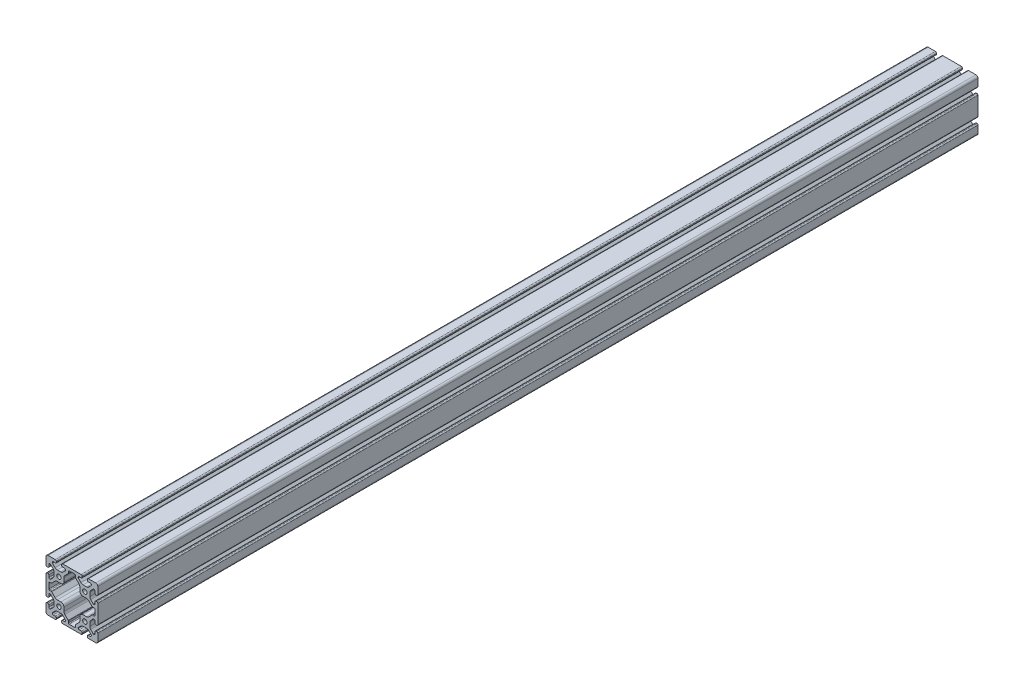
SolidWorks part; units mm, degrees
material "6061 Alloy"
ref_plane "Front Plane" through (0, 0, 0) normal (0, 0, 1) x (1, 0, 0)
ref_plane "Top Plane" through (0, 0, 0) normal (0, 1, 0) x (1, 0, 0)
ref_plane "Right Plane" through (0, 0, 0) normal (1, 0, 0) x (0, 0, -1)
sketch "Sketch1" plane through (0, 0, 0) normal (0, 0, 1) x (1, 0, 0)
  line L0 (0, -40) -> (0, 40) construction
  line L1 (0, 0) -> (-43.5804, 43.5804) construction
  line L2 (-20, 20) -> (-47.7323, 20) construction
  line L3 (-20, 20) -> (3.796, 43.796) construction
  line L4 (-20, 20) -> (-20, 43.5758) construction
  line L5 (-20, -27.7) -> (-20, -47.5576) construction
  line L7 (-36.8718, 24) -> (-28.8718, 24) construction
  line L8 (-36.8718, 24) -> (-36.8718, 16) construction
  line L9 (-36.8718, 16) -> (-28.8718, 16) construction
  line L10 (-28.8718, 24) -> (-28.8718, 16) construction
  line L11 (-36.8718, 24) -> (-28.8718, 16) construction
  line L12 (-36.8718, 16) -> (-28.8718, 24) construction
  line L131 (29.0912, 26.0365) -> (33.0827, 30.028)
  line L132 (27.7, 17.3222) -> (27.7, 22.6778)
  line L133 (29.0912, 13.9635) -> (33.0827, 9.972)
  line L134 (33.6201, 9.7494) -> (34.11, 9.7494)
  line L135 (35.68, 11.3194) -> (35.68, 14.2221)
  line L136 (37.25, 15.7921) -> (38.43, 15.7921)
  line L137 (40, 14.2221) -> (40, 7.0214)
  line L138 (40, 7.0214) -> (40, -7.0214)
  line L139 (40, -7.0214) -> (40, -14.2221)
  line L140 (38.43, -15.7921) -> (37.25, -15.7921)
  line L141 (35.68, -14.2221) -> (35.68, -11.3194)
  line L142 (33.6201, -9.7494) -> (34.11, -9.7494)
  line L143 (29.0912, -13.9635) -> (33.0827, -9.972)
  line L144 (27.7, -22.6778) -> (27.7, -17.3222)
  line L145 (29.0912, -26.0365) -> (33.0827, -30.028)
  line L146 (33.6201, -30.2506) -> (34.11, -30.2506)
  line L147 (35.68, -28.6806) -> (35.68, -25.7779)
  line L148 (37.25, -24.2079) -> (38.43, -24.2079)
  line L149 (40, -25.7779) -> (40, -33.0259)
  line L150 (40, -33.0259) -> (40, -36.83)
  line L151 (36.83, -40) -> (32.9998, -40)
  line L152 (32.9998, -40) -> (25.5696, -40)
  line L153 (23.9996, -38.43) -> (23.9996, -37.25)
  line L154 (25.5696, -35.68) -> (28.4723, -35.68)
  line L155 (30.0413, -34.0552) -> (30.0171, -33.3605)
  line L156 (29.7949, -32.8496) -> (26.0365, -29.0912)
  line L157 (17.3222, -27.7) -> (22.6778, -27.7)
  line L158 (10.035, -33.0197) -> (13.9635, -29.0912)
  line L159 (9.8124, -33.8926) -> (9.8124, -33.5571)
  line L160 (11.3824, -35.4626) -> (14.4246, -35.4626)
  line L161 (15.9946, -37.0326) -> (15.9946, -38.43)
  line L162 (14.4246, -40) -> (6.9987, -40)
  line L163 (6.9987, -40) -> (-6.9987, -40)
  line L164 (-6.9987, -40) -> (-14.4292, -40)
  line L165 (-15.9992, -38.43) -> (-15.9992, -37.25)
  line L166 (-14.4292, -35.68) -> (-11.5265, -35.68)
  line L167 (-9.9574, -34.0552) -> (-9.9816, -33.3618)
  line L168 (-10.2038, -32.8509) -> (-13.9635, -29.0912)
  line L169 (-22.6778, -27.7) -> (-17.3222, -27.7)
  line L170 (-30.028, -33.0827) -> (-26.0365, -29.0912)
  line L171 (-30.2506, -34.11) -> (-30.2506, -33.6201)
  line L172 (-28.6806, -35.68) -> (-25.7231, -35.68)
  line L173 (-24.1531, -37.25) -> (-24.1531, -38.43)
  line L174 (-25.7231, -40) -> (-33, -40)
  line L175 (-33, -40) -> (-36.83, -40)
  line L176 (-40, -36.83) -> (-40, -33.0191)
  line L177 (-40, -33.0191) -> (-40, -25.591)
  line L178 (-38.43, -24.021) -> (-37.25, -24.021)
  line L179 (-35.68, -28.4937) -> (-35.68, -25.591)
  line L180 (-34.0552, -30.0627) -> (-33.3827, -30.0392)
  line L181 (-32.8718, -29.8171) -> (-29.0912, -26.0365)
  line L182 (-27.7, -22.6778) -> (-27.7, -17.3222)
  line L183 (-29.0912, -13.9635) -> (-33.0827, -9.972)
  line L184 (-34.11, -9.7494) -> (-33.6201, -9.7494)
  line L185 (-35.68, -11.3194) -> (-35.68, -14.4473)
  line L186 (-38.43, -16.0173) -> (-37.25, -16.0173)
  line L187 (-40, -14.4473) -> (-40, -7.0169)
  line L188 (-40, -7.0169) -> (-40, 7.0169)
  line L189 (-40, 7.0169) -> (-40, 14.1348)
  line L190 (-38.1948, 15.94) -> (-36.9772, 15.94)
  line L191 (-35.68, 11.3194) -> (-35.68, 14.6428)
  line L192 (-34.11, 9.7494) -> (-33.6201, 9.7494)
  line L193 (-33.0827, 9.972) -> (-29.0912, 13.9635)
  line L194 (-27.7, 17.3222) -> (-27.7, 22.6778)
  line L195 (-29.0912, 26.0365) -> (-33.0827, 30.028)
  line L196 (-34.11, 30.2506) -> (-33.6201, 30.2506)
  line L197 (-35.68, 28.6806) -> (-35.68, 25.3572)
  line L198 (-38.1948, 24.06) -> (-36.9772, 24.06)
  line L199 (-40, 25.8652) -> (-40, 33.3181)
  line L200 (-40, 33.3181) -> (-40, 36.83)
  line L201 (-36.83, 40) -> (-33.0314, 40)
  line L202 (-33.0314, 40) -> (-25.8652, 40)
  line L203 (-24.06, 36.9772) -> (-24.06, 38.1948)
  line L204 (-25.3572, 35.68) -> (-28.7018, 35.68)
  line L205 (-30.285, 33.6069) -> (-30.285, 34.0968)
  line L206 (-30.0961, 33.1508) -> (-26.0365, 29.0912)
  line L207 (-22.6778, 27.7) -> (-17.3222, 27.7)
  line L208 (-13.9635, 29.0912) -> (-9.9039, 33.1508)
  line L209 (-9.715, 33.6069) -> (-9.715, 34.0968)
  line L210 (-14.6428, 35.68) -> (-11.2982, 35.68)
  line L211 (-15.94, 36.9772) -> (-15.94, 38.1948)
  line L212 (-14.1348, 40) -> (-6.9844, 40)
  line L213 (-6.9844, 40) -> (6.9844, 40)
  line L214 (6.9844, 40) -> (14.1348, 40)
  line L215 (15.94, 36.9772) -> (15.94, 38.1948)
  line L216 (14.6428, 35.68) -> (11.2982, 35.68)
  line L217 (9.715, 33.6069) -> (9.715, 34.0968)
  line L218 (9.9039, 33.1508) -> (13.9635, 29.0912)
  line L219 (17.3222, 27.7) -> (22.6778, 27.7)
  line L220 (26.0365, 29.0912) -> (30.028, 33.0827)
  line L221 (30.2506, 33.6201) -> (30.2506, 34.11)
  line L222 (25.5409, 35.679) -> (28.6258, 35.679)
  line L223 (23.9709, 37.249) -> (23.9709, 38.43)
  line L224 (25.5409, 40) -> (36.83, 40)
  line L226 (40, 36.83) -> (40, 32.9339)
  line L227 (40, 32.9339) -> (40, 25.7779)
  line L228 (38.43, 24.2079) -> (37.0956, 24.2079)
  line L229 (35.5256, 25.7779) -> (35.5256, 28.6806)
  line L230 (33.6201, 30.2506) -> (33.9556, 30.2506)
  line L231 (17.07, 12.32) -> (22.6578, 12.32)
  line L232 (26.0165, 10.9288) -> (31.1439, 5.8014)
  line L233 (32.0419, 5.4294) -> (34.41, 5.4294)
  line L234 (35.68, -4.1594) -> (35.68, 4.1594)
  line L235 (32.0419, -5.4294) -> (34.41, -5.4294)
  line L236 (26.0165, -10.9288) -> (31.1439, -5.8014)
  line L237 (17.07, -12.32) -> (22.6578, -12.32)
  line L238 (12.32, -22.6578) -> (12.32, -17.07)
  line L239 (5.8014, -31.1439) -> (10.9288, -26.0165)
  line L240 (5.4294, -34.41) -> (5.4294, -32.0419)
  line L241 (-4.1594, -35.68) -> (4.1594, -35.68)
  line L242 (-5.4294, -34.41) -> (-5.4294, -32.0419)
  line L243 (-5.8014, -31.1439) -> (-10.9288, -26.0165)
  line L244 (-12.32, -22.6578) -> (-12.32, -17.07)
  line L245 (-22.6578, -12.32) -> (-17.07, -12.32)
  line L246 (-26.0165, -10.9288) -> (-31.1439, -5.8014)
  line L247 (-34.41, -5.4294) -> (-32.0419, -5.4294)
  line L248 (-35.68, -4.1594) -> (-35.68, 4.1594)
  line L249 (-34.41, 5.4294) -> (-32.0419, 5.4294)
  line L250 (-31.1439, 5.8014) -> (-26.0165, 10.9288)
  line L251 (-22.6578, 12.32) -> (-17.07, 12.32)
  line L252 (-12.32, 17.07) -> (-12.32, 22.6578)
  line L253 (-10.9288, 26.0165) -> (-5.8014, 31.1439)
  line L254 (-5.4294, 32.0419) -> (-5.4294, 34.41)
  line L255 (-4.1594, 35.68) -> (4.1594, 35.68)
  line L256 (5.4294, 32.0419) -> (5.4294, 34.41)
  line L257 (5.8014, 31.1439) -> (10.9288, 26.0165)
  line L258 (12.32, 17.07) -> (12.32, 22.6578)
  line L260 (-40, 0) -> (40, 0) construction
  circle A0 centre (-32.8718, 20) radius 4 construction
  circle A116 centre (-20, 20) radius 3.4
  circle A117 centre (20, 20) radius 3.4
  circle A118 centre (20, -20) radius 3.4
  circle A119 centre (-20, -20) radius 3.4
  arc A120 (29.0912, 26.0365) -> (27.7, 22.6778) centre (32.45, 22.6778) ccw
  arc A121 (27.7, 17.3222) -> (29.0912, 13.9635) centre (32.45, 17.3222) ccw
  arc A122 (33.0827, 9.972) -> (33.6201, 9.7494) centre (33.6201, 10.5094) ccw
  arc A123 (34.11, 9.7494) -> (35.68, 11.3194) centre (34.11, 11.3194) ccw
  arc A124 (37.25, 15.7921) -> (35.68, 14.2221) centre (37.25, 14.2221) ccw
  arc A125 (40, 14.2221) -> (38.43, 15.7921) centre (38.43, 14.2221) ccw
  arc A126 (38.43, -15.7921) -> (40, -14.2221) centre (38.43, -14.2221) ccw
  arc A127 (35.68, -14.2221) -> (37.25, -15.7921) centre (37.25, -14.2221) ccw
  arc A128 (35.68, -11.3194) -> (34.11, -9.7494) centre (34.11, -11.3194) ccw
  arc A129 (33.6201, -9.7494) -> (33.0827, -9.972) centre (33.6201, -10.5094) ccw
  arc A130 (29.0912, -13.9635) -> (27.7, -17.3222) centre (32.45, -17.3222) ccw
  arc A131 (27.7, -22.6778) -> (29.0912, -26.0365) centre (32.45, -22.6778) ccw
  arc A132 (33.0827, -30.028) -> (33.6201, -30.2506) centre (33.6201, -29.4906) ccw
  arc A133 (34.11, -30.2506) -> (35.68, -28.6806) centre (34.11, -28.6806) ccw
  arc A134 (37.25, -24.2079) -> (35.68, -25.7779) centre (37.25, -25.7779) ccw
  arc A135 (40, -25.7779) -> (38.43, -24.2079) centre (38.43, -25.7779) ccw
  arc A136 (36.83, -40) -> (40, -36.83) centre (36.83, -36.83) ccw
  arc A137 (23.9996, -38.43) -> (25.5696, -40) centre (25.5696, -38.43) ccw
  arc A138 (25.5696, -35.68) -> (23.9996, -37.25) centre (25.5696, -37.25) ccw
  arc A139 (28.4723, -35.68) -> (30.0413, -34.0552) centre (28.4723, -34.11) ccw
  arc A140 (30.0171, -33.3605) -> (29.7949, -32.8496) centre (29.2575, -33.387) ccw
  arc A141 (26.0365, -29.0912) -> (22.6778, -27.7) centre (22.6778, -32.45) ccw
  arc A142 (17.3222, -27.7) -> (13.9635, -29.0912) centre (17.3222, -32.45) ccw
  arc A143 (10.035, -33.0197) -> (9.8124, -33.5571) centre (10.5724, -33.5571) ccw
  arc A144 (9.8124, -33.8926) -> (11.3824, -35.4626) centre (11.3824, -33.8926) ccw
  arc A145 (15.9946, -37.0326) -> (14.4246, -35.4626) centre (14.4246, -37.0326) ccw
  arc A146 (14.4246, -40) -> (15.9946, -38.43) centre (14.4246, -38.43) ccw
  arc A147 (-15.9992, -38.43) -> (-14.4292, -40) centre (-14.4292, -38.43) ccw
  arc A148 (-14.4292, -35.68) -> (-15.9992, -37.25) centre (-14.4292, -37.25) ccw
  arc A149 (-11.5265, -35.68) -> (-9.9574, -34.0552) centre (-11.5265, -34.11) ccw
  arc A150 (-9.9816, -33.3618) -> (-10.2038, -32.8509) centre (-10.7412, -33.3883) ccw
  arc A151 (-13.9635, -29.0912) -> (-17.3222, -27.7) centre (-17.3222, -32.45) ccw
  arc A152 (-22.6778, -27.7) -> (-26.0365, -29.0912) centre (-22.6778, -32.45) ccw
  arc A153 (-30.028, -33.0827) -> (-30.2506, -33.6201) centre (-29.4906, -33.6201) ccw
  arc A154 (-30.2506, -34.11) -> (-28.6806, -35.68) centre (-28.6806, -34.11) ccw
  arc A155 (-24.1531, -37.25) -> (-25.7231, -35.68) centre (-25.7231, -37.25) ccw
  arc A156 (-25.7231, -40) -> (-24.1531, -38.43) centre (-25.7231, -38.43) ccw
  arc A157 (-40, -36.83) -> (-36.83, -40) centre (-36.83, -36.83) ccw
  arc A158 (-38.43, -24.021) -> (-40, -25.591) centre (-38.43, -25.591) ccw
  arc A159 (-35.68, -25.591) -> (-37.25, -24.021) centre (-37.25, -25.591) ccw
  arc A160 (-35.68, -28.4937) -> (-34.0552, -30.0627) centre (-34.11, -28.4937) ccw
  arc A161 (-33.3827, -30.0392) -> (-32.8718, -29.8171) centre (-33.4092, -29.2797) ccw
  arc A162 (-29.0912, -26.0365) -> (-27.7, -22.6778) centre (-32.45, -22.6778) ccw
  arc A163 (-27.7, -17.3222) -> (-29.0912, -13.9635) centre (-32.45, -17.3222) ccw
  arc A164 (-33.0827, -9.972) -> (-33.6201, -9.7494) centre (-33.6201, -10.5094) ccw
  arc A165 (-34.11, -9.7494) -> (-35.68, -11.3194) centre (-34.11, -11.3194) ccw
  arc A166 (-37.25, -16.0173) -> (-35.68, -14.4473) centre (-37.25, -14.4473) ccw
  arc A167 (-40, -14.4473) -> (-38.43, -16.0173) centre (-38.43, -14.4473) ccw
  arc A168 (-38.1948, 15.94) -> (-40, 14.1348) centre (-38.1948, 14.1348) ccw
  arc A169 (-35.68, 14.6428) -> (-36.9772, 15.94) centre (-36.9772, 14.6428) ccw
  arc A170 (-35.68, 11.3194) -> (-34.11, 9.7494) centre (-34.11, 11.3194) ccw
  arc A171 (-33.6201, 9.7494) -> (-33.0827, 9.972) centre (-33.6201, 10.5094) ccw
  arc A172 (-29.0912, 13.9635) -> (-27.7, 17.3222) centre (-32.45, 17.3222) ccw
  arc A173 (-27.7, 22.6778) -> (-29.0912, 26.0365) centre (-32.45, 22.6778) ccw
  arc A174 (-33.0827, 30.028) -> (-33.6201, 30.2506) centre (-33.6201, 29.4906) ccw
  arc A175 (-34.11, 30.2506) -> (-35.68, 28.6806) centre (-34.11, 28.6806) ccw
  arc A176 (-36.9772, 24.06) -> (-35.68, 25.3572) centre (-36.9772, 25.3572) ccw
  arc A177 (-40, 25.8652) -> (-38.1948, 24.06) centre (-38.1948, 25.8652) ccw
  arc A178 (-36.83, 40) -> (-40, 36.83) centre (-36.83, 36.83) ccw
  arc A179 (-24.06, 38.1948) -> (-25.8652, 40) centre (-25.8652, 38.1948) ccw
  arc A180 (-25.3572, 35.68) -> (-24.06, 36.9772) centre (-25.3572, 36.9772) ccw
  arc A181 (-28.7018, 35.68) -> (-30.285, 34.0968) centre (-28.7018, 34.0968) ccw
  arc A182 (-30.285, 33.6069) -> (-30.0961, 33.1508) centre (-29.6399, 33.6069) ccw
  arc A183 (-26.0365, 29.0912) -> (-22.6778, 27.7) centre (-22.6778, 32.45) ccw
  arc A184 (-17.3222, 27.7) -> (-13.9635, 29.0912) centre (-17.3222, 32.45) ccw
  arc A185 (-9.9039, 33.1508) -> (-9.715, 33.6069) centre (-10.3601, 33.6069) ccw
  arc A186 (-9.715, 34.0968) -> (-11.2982, 35.68) centre (-11.2982, 34.0968) ccw
  arc A187 (-15.94, 36.9772) -> (-14.6428, 35.68) centre (-14.6428, 36.9772) ccw
  arc A188 (-14.1348, 40) -> (-15.94, 38.1948) centre (-14.1348, 38.1948) ccw
  arc A189 (15.94, 38.1948) -> (14.1348, 40) centre (14.1348, 38.1948) ccw
  arc A190 (14.6428, 35.68) -> (15.94, 36.9772) centre (14.6428, 36.9772) ccw
  arc A191 (11.2982, 35.68) -> (9.715, 34.0968) centre (11.2982, 34.0968) ccw
  arc A192 (9.715, 33.6069) -> (9.9039, 33.1508) centre (10.3601, 33.6069) ccw
  arc A193 (13.9635, 29.0912) -> (17.3222, 27.7) centre (17.3222, 32.45) ccw
  arc A194 (22.6778, 27.7) -> (26.0365, 29.0912) centre (22.6778, 32.45) ccw
  arc A195 (30.028, 33.0827) -> (30.2506, 33.6201) centre (29.4906, 33.6201) ccw
  arc A196 (30.2506, 34.11) -> (28.6258, 35.679) centre (28.6806, 34.11) ccw
  arc A197 (23.9709, 37.249) -> (25.5409, 35.679) centre (25.5409, 37.249) ccw
  arc A198 (25.5409, 40) -> (23.9709, 38.43) centre (25.5409, 38.43) ccw
  arc A199 (40, 36.83) -> (36.83, 40) centre (36.83, 36.83) ccw
  arc A200 (38.43, 24.2079) -> (40, 25.7779) centre (38.43, 25.7779) ccw
  arc A201 (35.5256, 25.7779) -> (37.0956, 24.2079) centre (37.0956, 25.7779) ccw
  arc A202 (35.5256, 28.6806) -> (33.9556, 30.2506) centre (33.9556, 28.6806) ccw
  arc A203 (33.6201, 30.2506) -> (33.0827, 30.028) centre (33.6201, 29.4906) ccw
  arc A204 (26.0165, 10.9288) -> (22.6578, 12.32) centre (22.6578, 7.57) ccw
  arc A205 (31.1439, 5.8014) -> (32.0419, 5.4294) centre (32.0419, 6.6994) ccw
  arc A206 (35.68, 4.1594) -> (34.41, 5.4294) centre (34.41, 4.1594) ccw
  arc A207 (34.41, -5.4294) -> (35.68, -4.1594) centre (34.41, -4.1594) ccw
  arc A208 (32.0419, -5.4294) -> (31.1439, -5.8014) centre (32.0419, -6.6994) ccw
  arc A209 (22.6578, -12.32) -> (26.0165, -10.9288) centre (22.6578, -7.57) ccw
  arc A210 (17.07, -12.32) -> (12.32, -17.07) centre (17.07, -17.07) ccw
  arc A211 (10.9288, -26.0165) -> (12.32, -22.6578) centre (7.57, -22.6578) ccw
  arc A212 (5.8014, -31.1439) -> (5.4294, -32.0419) centre (6.6994, -32.0419) ccw
  arc A213 (4.1594, -35.68) -> (5.4294, -34.41) centre (4.1594, -34.41) ccw
  arc A214 (-5.4294, -34.41) -> (-4.1594, -35.68) centre (-4.1594, -34.41) ccw
  arc A215 (-5.4294, -32.0419) -> (-5.8014, -31.1439) centre (-6.6994, -32.0419) ccw
  arc A216 (-12.32, -22.6578) -> (-10.9288, -26.0165) centre (-7.57, -22.6578) ccw
  arc A217 (-12.32, -17.07) -> (-17.07, -12.32) centre (-17.07, -17.07) ccw
  arc A218 (-26.0165, -10.9288) -> (-22.6578, -12.32) centre (-22.6578, -7.57) ccw
  arc A219 (-31.1439, -5.8014) -> (-32.0419, -5.4294) centre (-32.0419, -6.6994) ccw
  arc A220 (-35.68, -4.1594) -> (-34.41, -5.4294) centre (-34.41, -4.1594) ccw
  arc A221 (-34.41, 5.4294) -> (-35.68, 4.1594) centre (-34.41, 4.1594) ccw
  arc A222 (-32.0419, 5.4294) -> (-31.1439, 5.8014) centre (-32.0419, 6.6994) ccw
  arc A223 (-22.6578, 12.32) -> (-26.0165, 10.9288) centre (-22.6578, 7.57) ccw
  arc A224 (-17.07, 12.32) -> (-12.32, 17.07) centre (-17.07, 17.07) ccw
  arc A225 (-10.9288, 26.0165) -> (-12.32, 22.6578) centre (-7.57, 22.6578) ccw
  arc A226 (-5.8014, 31.1439) -> (-5.4294, 32.0419) centre (-6.6994, 32.0419) ccw
  arc A227 (-4.1594, 35.68) -> (-5.4294, 34.41) centre (-4.1594, 34.41) ccw
  arc A228 (5.4294, 34.41) -> (4.1594, 35.68) centre (4.1594, 34.41) ccw
  arc A229 (5.4294, 32.0419) -> (5.8014, 31.1439) centre (6.6994, 32.0419) ccw
  arc A230 (12.32, 22.6578) -> (10.9288, 26.0165) centre (7.57, 22.6578) ccw
  arc A231 (12.32, 17.07) -> (17.07, 12.32) centre (17.07, 17.07) ccw
  point P9 (-32.8718, 20)
  dimension "D8" = 6.8
  dimension "D1" = 80
  dimension "D2" = 40
  dimension "D3" = 20
  dimension "D4" = 20.57
  dimension "D5" = 4.32
  dimension "D6" = 4.32
  dimension "D7" = 8.12
  dimension "D9" = 4.32
  dimension "D10" = 12.3
  dimension "D11" = 8
  dimension "D12" = 8
extrude "Extrude1" add sketch "Sketch1" against normal blind 1360
